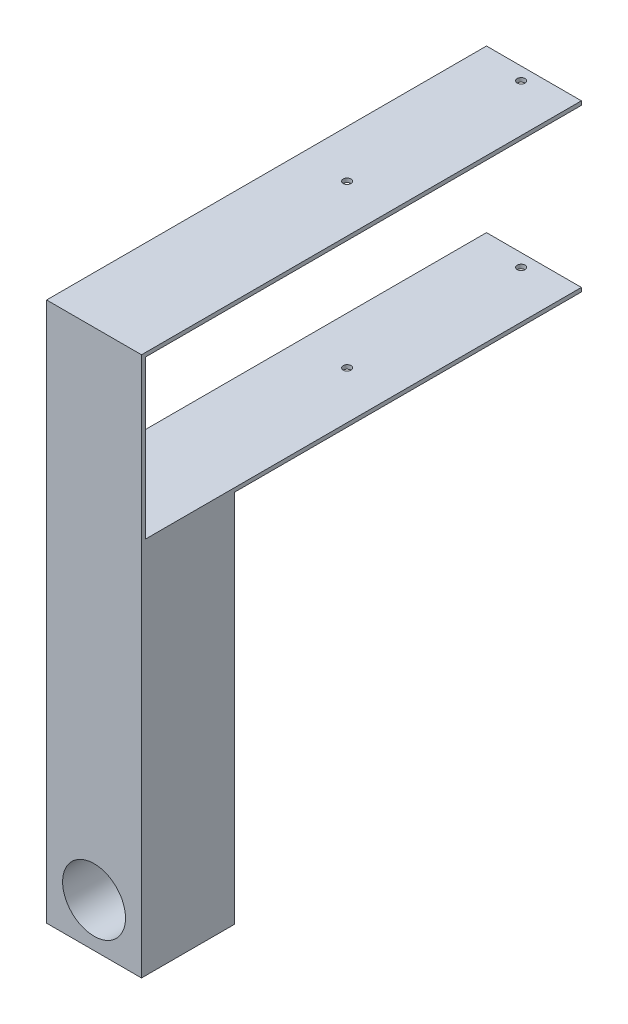
SolidWorks part; units mm, degrees
material "Malleable Cast Iron"
ref_plane "Front Plane" through (0, 0, 0) normal (0, 0, 1) x (1, 0, 0)
ref_plane "Top Plane" through (0, 0, 0) normal (0, 1, 0) x (1, 0, 0)
ref_plane "Right Plane" through (0, 0, 0) normal (1, 0, 0) x (0, 0, -1)
sketch "Sketch1" plane through (0, 0, 0) normal (0, 0, 1) x (1, 0, 0)
  line L1 (-1935.48, -11007.09) -> (1935.48, -11007.09)
  line L2 (-1935.48, -11007.09) -> (-1935.48, 11007.09)
  line L3 (-1935.48, 11007.09) -> (1935.48, 11007.09)
  line L4 (1935.48, -11007.09) -> (1935.48, 11007.09)
  line L5 (-1935.48, -11007.09) -> (1935.48, 11007.09) construction
  line L6 (-1935.48, 11007.09) -> (1935.48, -11007.09) construction
  point P0 (0, 0)
  dimension "D1" = 3870.96
  dimension "D2" = 22014.18
extrude "Boss-Extrude1" add sketch "Sketch1" along normal blind 161.29
ref_plane "Plane1" through (0, 4415.536, 0) normal (0, 1, 0) x (1, 0, 0)
ref_plane "Plane2" through (0, 11007.09, 0) normal (0, 1, 0) x (1, 0, 0)
sketch "Sketch2" plane through (0, 11007.09, 0) normal (0, 1, 0) x (1, 0, 0)
  line L0 (0, 0) -> (0, 17780) construction
  line L1 (1935.48, 0) -> (-1935.48, 0)
  line L2 (1935.48, 0) -> (1935.48, 17780)
  line L3 (1935.48, 17780) -> (-1935.48, 17780)
  line L4 (-1935.48, 0) -> (-1935.48, 17780)
  dimension "D2" = 1935.48
  dimension "D1" = 17780
extrude "Boss-Extrude2" add sketch "Sketch2" against normal blind 161.29
sketch "Sketch3" plane through (0, 4415.536, 0) normal (0, 1, 0) x (1, 0, 0)
  line L0 (-1935.48, 0) -> (1935.48, 0)
  line L20 (1935.48, 0) -> (1935.48, 17780)
  line L21 (1935.48, 17780) -> (-1935.48, 17780)
  line L22 (-1935.48, 0) -> (-1935.48, 17780)
  point P0 (0, 0)
  point P7 (0, 0)
  dimension "D1" = 17780
  dimension "D2" = 3870.96
extrude "Boss-Extrude3" add sketch "Sketch3" against normal blind 161.29
sketch "Sketch4" plane through (0, 4254.246, 0) normal (0, -1, 0) x (1, 0, 0)
  line L0 (-1935.48, 0) -> (1935.48, 0) construction
  line L2 (1935.48, 68.8203) -> (1935.48, -3640.8497)
  line L3 (1935.48, -3640.8497) -> (-1935.48, -3640.8497)
  line L4 (-1935.48, 68.8203) -> (-1935.48, -3640.8497)
  line L7 (-1935.48, -17780) -> (-1935.48, 0) construction
  line L8 (1935.48, 68.8203) -> (-1935.48, 68.8203)
  dimension "D1" = 3709.67
  dimension "D2" = 3870.96
  dimension "D3" = 68.8203
extrude "Boss-Extrude4" add sketch "Sketch4" along normal up to vertex (15261.336 mm away) contours L4 L3 L2 L8 up to point (-1935.48, -11007.09, 0)
sketch "Sketch5" plane through (0, 11007.09, 0) normal (0, 1, 0) x (1, 0, 0)
  line L0 (0, 0) -> (0, 17780) construction
  line L1 (1935.48, 17780) -> (-1935.48, 17780) construction
  circle A0 centre (0, 17258.03) radius 161.29
  circle A1 centre (0, 10161.27) radius 161.29
  dimension "D2" = 322.58
  dimension "D4" = 322.58
  dimension "D1" = 521.97
  dimension "D3" = 7096.76
extrude "Cut-Extrude1" cut sketch "Sketch5" against normal blind 12848.844
sketch "Sketch7" plane through (0, 0, 161.29) normal (0, 0, 1) x (1, 0, 0)
  line L0 (-1935.48, -11007.09) -> (1935.48, -11007.09) construction
  circle A0 centre (0, -9216.39) radius 1282.7
  dimension "D3" = 2565.4
  dimension "D1" = 1790.7
  dimension "D2" = 1935.48
extrude "Cut-Extrude2" cut sketch "Sketch7" against normal through all
scale "Scale1" scale about centroid uniform scaling yes scale factor 0.03937
